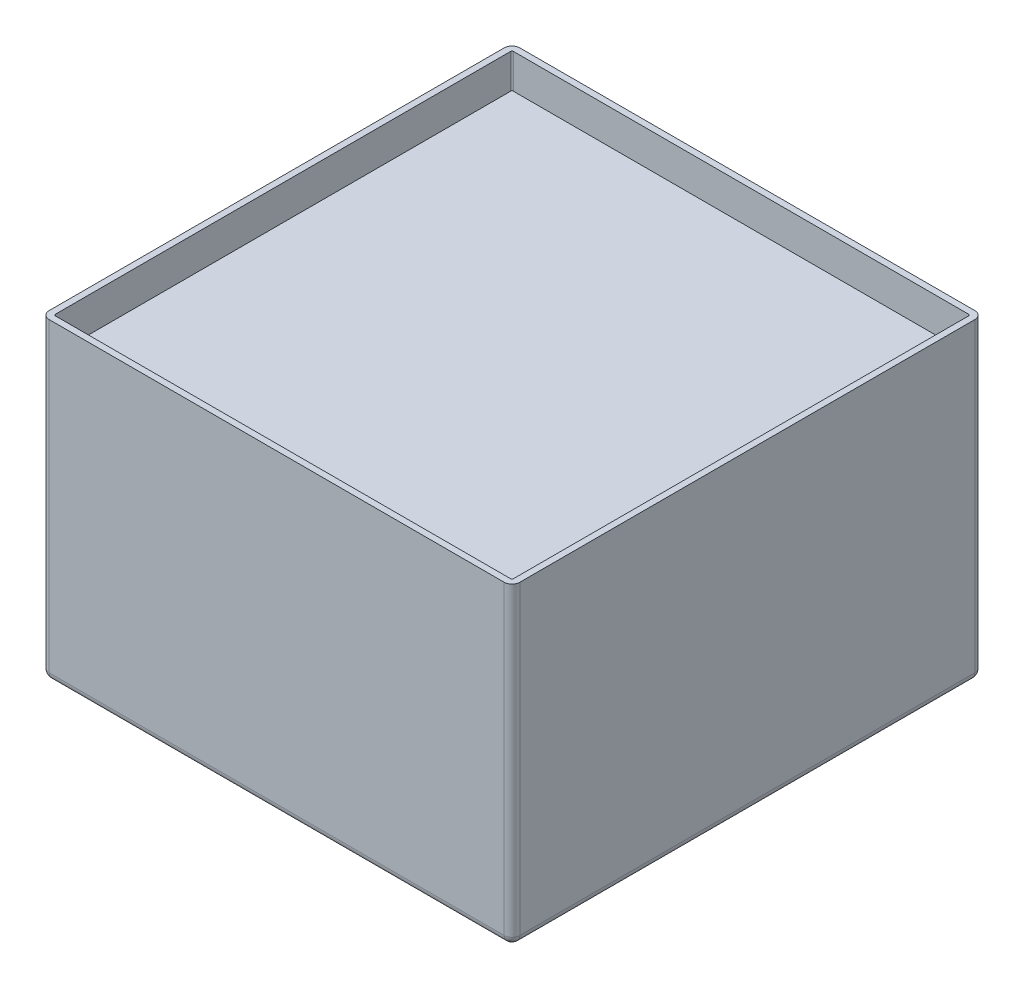
SolidWorks part; units mm, degrees
ref_plane "Alzado" through (0, 0, 0) normal (0, 0, 1) x (1, 0, 0)
ref_plane "Planta" through (0, 0, 0) normal (0, 1, 0) x (1, 0, 0)
ref_plane "Vista lateral" through (0, 0, 0) normal (1, 0, 0) x (0, 0, -1)
sketch "Croquis1" plane through (0, 0, 0) normal (0, 1, 0) x (1, 0, 0)
  line L1 (300, -300) -> (-300, -300)
  line L2 (300, -300) -> (300, 300)
  line L3 (300, 300) -> (-300, 300)
  line L4 (-300, -300) -> (-300, 300)
  line L5 (300, -300) -> (-300, 300) construction
  line L6 (300, 300) -> (-300, -300) construction
  point P0 (0, 0)
  dimension "D1" = 600
  dimension "D2" = 600
extrude "Extruir1" add sketch "Croquis1" along normal blind 400
fillet "Redondeo1" radius 10 8 edges at (0, 0, 300) (300, 0, 0) (0, 0, -300) (-300, 0, 0) (-300, 200, -300) (300, 200, -300) (300, 200, 300) (-300, 200, 300)
shell "Vaciado1" thickness 8
sketch "Croquis2" plane through (0, 8, 0) normal (0, 1, 0) x (1, 0, 0)
  line L4 (290, -290) -> (290, 290)
  line L5 (290, 290) -> (-290, 290)
  line L6 (-290, 290) -> (-290, -290)
  line L7 (-290, -290) -> (290, -290)
  line L8 (290, -290) -> (290, 290)
  line L9 (290, 290) -> (-290, 290)
  line L10 (-290, 290) -> (-290, -290)
  line L11 (-290, -290) -> (290, -290)
  dimension "D1" = 0
extrude "Extruir2" add sketch "Croquis2" along normal blind 350 separate body
